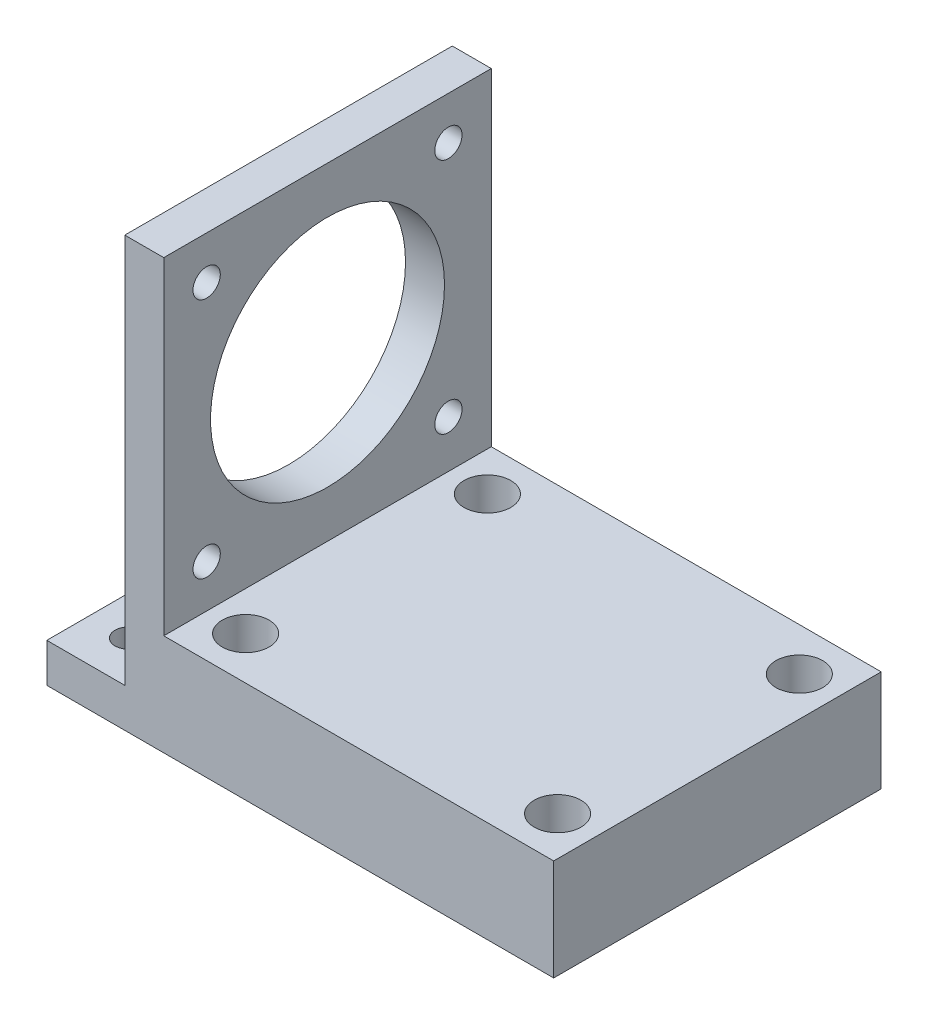
SolidWorks part; units mm, degrees
ref_plane "Plano frontal" through (0, 0, 0) normal (0, 0, 1) x (1, 0, 0)
ref_plane "Plano superior" through (0, 0, 0) normal (0, 1, 0) x (1, 0, 0)
ref_plane "Plano direito" through (0, 0, 0) normal (1, 0, 0) x (0, 0, -1)
sketch "Esboço1" plane through (0, 0, 0) normal (0, 1, 0) x (1, 0, 0)
  line L1 (32.5, 21) -> (-32.5, 21)
  line L2 (32.5, 21) -> (32.5, -21)
  line L3 (32.5, -21) -> (-32.5, -21)
  line L4 (-32.5, 21) -> (-32.5, -21)
  line L5 (32.5, 21) -> (-32.5, -21) construction
  line L6 (32.5, -21) -> (-32.5, 21) construction
  point P0 (0, 0)
  dimension "D1" = 42
  dimension "D2" = 65
extrude "Ressalto-extrusão1" add sketch "Esboço1" along normal blind 55
sketch "Esboço2" plane through (-32.5, 0, 0) normal (-1, 0, 0) x (0, 0, 1)
  line L0 (-21, 55) -> (21, 55) construction
  line L1 (-21, 55) -> (21, 55)
  line L2 (-21, 55) -> (-21, 5)
  line L3 (-21, 5) -> (21, 5)
  line L4 (21, 55) -> (21, 5)
  line L5 (-21, 55) -> (21, 5) construction
  line L6 (-21, 5) -> (21, 55) construction
  point P0 (0, 30)
  point P5 (0, 0)
  dimension "D1" = 42
  dimension "D2" = 50
extrude "Corte-extrusão1" cut sketch "Esboço2" against normal blind 10
sketch "Esboço3" plane through (32.5, 0, 0) normal (1, 0, 0) x (0, 0, -1)
  line L0 (21, 55) -> (21, 0) construction
  line L1 (-21, 55) -> (21, 55)
  line L2 (-21, 55) -> (-21, 13)
  line L3 (-21, 13) -> (21, 13)
  line L4 (21, 55) -> (21, 13)
  line L5 (-21, 55) -> (21, 13) construction
  line L6 (-21, 13) -> (21, 55) construction
  line L7 (-21, 55) -> (21, 55) construction
  point P0 (0, 34)
  point P7 (0, 0)
  dimension "D1" = 42
  dimension "D2" = 42
extrude "Corte-extrusão2" cut sketch "Esboço3" against normal blind 50
sketch "Esboço4" plane through (-17.5, 0, 0) normal (1, 0, 0) x (0, 0, -1)
  line L0 (-21, 55) -> (-21, 13) construction
  line L3 (21, 55) -> (-21, 55) construction
  circle A0 centre (-15.5, 49.5) radius 1.75
  circle A1 centre (15.5, 49.5) radius 1.75
  circle A2 centre (15.5, 19.0707) radius 1.75
  circle A3 centre (-15.5, 18.5) radius 1.75
  point P8 (0, 0)
  point P9 (0, 0)
  point P10 (0, 0)
  dimension "D1" = 3.5
  dimension "D2" = 3.5
  dimension "D3" = 3.5
  dimension "D4" = 3.5
  dimension "D5" = 31
  dimension "D6" = 31
  dimension "D7" = 5.5
  dimension "D8" = 5.5
extrude "Corte-extrusão3" cut sketch "Esboço4" against normal through all
sketch "Esboço5" plane through (0, 5, 0) normal (0, 1, 0) x (1, 0, 0)
  line L0 (-22.5, 21) -> (-32.5, 21) construction
  line L1 (-32.5, 21) -> (-32.5, -21) construction
  circle A0 centre (-27.5, 15.5) radius 1.75
  circle A1 centre (-27.5, -15.5) radius 1.75
  dimension "D3" = 3.5
  dimension "D4" = 3.5
  dimension "D1" = 31
  dimension "D2" = 5.5
  dimension "D5" = 5
extrude "Corte-extrusão4" cut sketch "Esboço5" against normal through all
sketch "Esboço6" plane through (0, 13, 0) normal (0, 1, 0) x (1, 0, 0)
  line L0 (-17.5, 21) -> (32.5, 21) construction
  line L1 (-17.5, 21) -> (-17.5, -21) construction
  circle A0 centre (-12.5, 15.5) radius 1.75
  circle A1 centre (27.5, 15.5) radius 1.75
  circle A2 centre (27.5, -15.5) radius 1.75
  circle A3 centre (-12.5, -15.5) radius 1.75
  dimension "D3" = 3.5
  dimension "D1" = 5.5
  dimension "D2" = 5
  dimension "D4" = 2
  dimension "D5" = 2
extrude "Corte-extrusão5" cut sketch "Esboço6" against normal through all
sketch "Esboço7" plane through (0, 13, 0) normal (0, 1, 0) x (1, 0, 0)
  line L0 (-17.5, 21) -> (32.5, 21) construction
  line L1 (-17.5, 21) -> (-17.5, -21) construction
  circle A0 centre (-12.5, 15.5) radius 3
  circle A1 centre (27.5, 15.5) radius 3
  circle A2 centre (27.5, -15.5) radius 3
  circle A3 centre (-12.5, -15.5) radius 3
  dimension "D1" = 6
  dimension "D2" = 5.5
  dimension "D3" = 5
  dimension "D4" = 2
  dimension "D5" = 2
extrude "Corte-extrusão6" cut sketch "Esboço7" against normal blind 8
sketch "Esboço8" plane through (-17.5, 0, 0) normal (1, 0, 0) x (0, 0, -1)
  line L0 (-21, 34) -> (0, 34) construction
  line L1 (-21, 55) -> (-21, 13) construction
  line L2 (0, 34) -> (0, 13) construction
  line L3 (-21, 13) -> (21, 13) construction
  circle A0 centre (0, 34) radius 15
  dimension "D1" = 30
extrude "Corte-extrusão7" cut sketch "Esboço8" against normal through all
